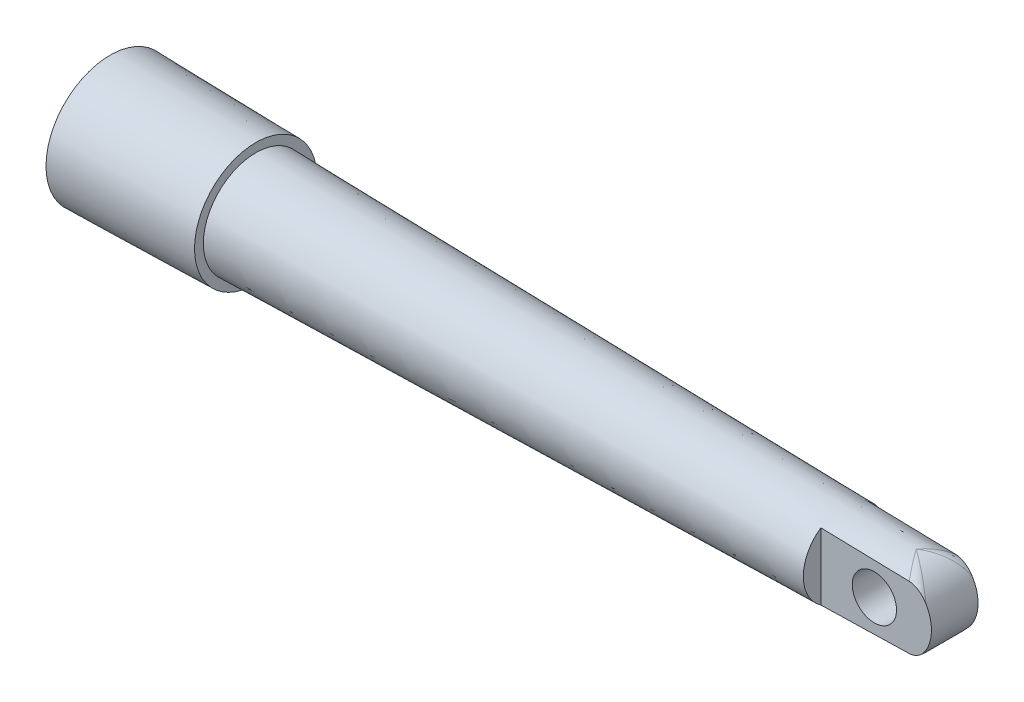
SolidWorks part; units mm, degrees
ref_plane "Front Plane" through (0, 0, 0) normal (0, 0, 1) x (1, 0, 0)
ref_plane "Top Plane" through (0, 0, 0) normal (0, 1, 0) x (1, 0, 0)
ref_plane "Right Plane" through (0, 0, 0) normal (1, 0, 0) x (0, 0, -1)
sketch "Sketch1" plane through (0, 0, 0) normal (0, 0, 1) x (1, 0, 0)
  line L0 (0, 0) -> (31.5, 0)
  line L1 (31.5, 0) -> (31.5, 1.75)
  line L2 (31.5, 1.75) -> (6.25, 2.25)
  line L3 (6.25, 2.25) -> (6.25, 2.63)
  line L4 (6.25, 2.63) -> (0, 2.7538)
  line L5 (0, 2.7538) -> (0, 0)
  dimension "D1" = 31.5
  dimension "D2" = 1.75
  dimension "D3" = 2.25
  dimension "D4" = 2.63
  dimension "D5" = 6.25
  dimension "D6" = 2.7538
revolve "Revolve1" add sketch "Sketch1" angle 360 about L0
sketch "Sketch2" plane through (0, 0, 0) normal (0, 0, 1) x (1, 0, 0)
  line L0 (31.5, 0) -> (36.25, 0) construction
  line L1 (31.5, -1.75) -> (31.5, 1.75) construction
  line L2 (31.5, 1.75) -> (34.5944, 1.6887)
  line L3 (31.5, 1.75) -> (6.25, 2.25) construction
  line L4 (31.5, -1.75) -> (34.5944, -1.6887)
  line L5 (31.5, 1.75) -> (31.5, -1.75)
  arc A0 (34.5944, -1.6887) -> (34.5944, 1.6887) centre (34.5609, 0) ccw
  dimension "D1" = 4.75
extrude "Boss-Extrude1" add sketch "Sketch2" along normal mid plane 2
sketch "Sketch3" plane through (0, 0, 0) normal (0, 0, 1) x (1, 0, 0)
  line L0 (31.5, 0) -> (42.2677, 0) construction
  line L1 (31.5, -1.4361) -> (31.5, 1.4361) construction
  line L2 (31.5, 1.75) -> (31.5, 3.029)
  line L3 (31.5, 3.029) -> (37.1605, 3.029)
  line L4 (37.1605, 3.029) -> (37.1605, 1.6379)
  line L5 (37.1605, 1.6379) -> (31.5, 1.75)
  line L6 (34.5944, 1.6887) -> (31.5, 1.75) construction
revolve "Cut-Revolve1" cut sketch "Sketch3" angle 360 about L0
sketch "Sketch4" plane through (0, 0, 1) normal (0, 0, 1) x (1, 0, 0)
  line L0 (31.5, 0) -> (35.522, 0) construction
  line L2 (31.5, -1.4361) -> (31.5, 1.4361) construction
  circle A0 centre (33.8, 0) radius 0.95
  arc A1 (35.5942, -1.3362) -> (35.5942, 1.3362) centre (34.5609, 0) ccw construction
  point P10 (36.25, 0)
  dimension "D1" = 1.9
  dimension "D2" = 2.45
extrude "Cut-Extrude1" cut sketch "Sketch4" against normal through all both and the other way through all
fillet "Fillet1" radius 0.5 4 edges at (35.3595, 1.4884, -0.7653) (35.0442, -1.6185, -0.4499) (35.0442, 1.6185, 0.4499) (35.3595, -1.4884, 0.7653)
sketch "Sketch5" plane through (0, 0, 0) normal (-1, 0, 0) x (0, 0, 1)
  circle A0 centre (0, 0) radius 1
  dimension "D1" = 2
extrude "Cut-Extrude2" cut sketch "Sketch5" against normal blind 26.5
